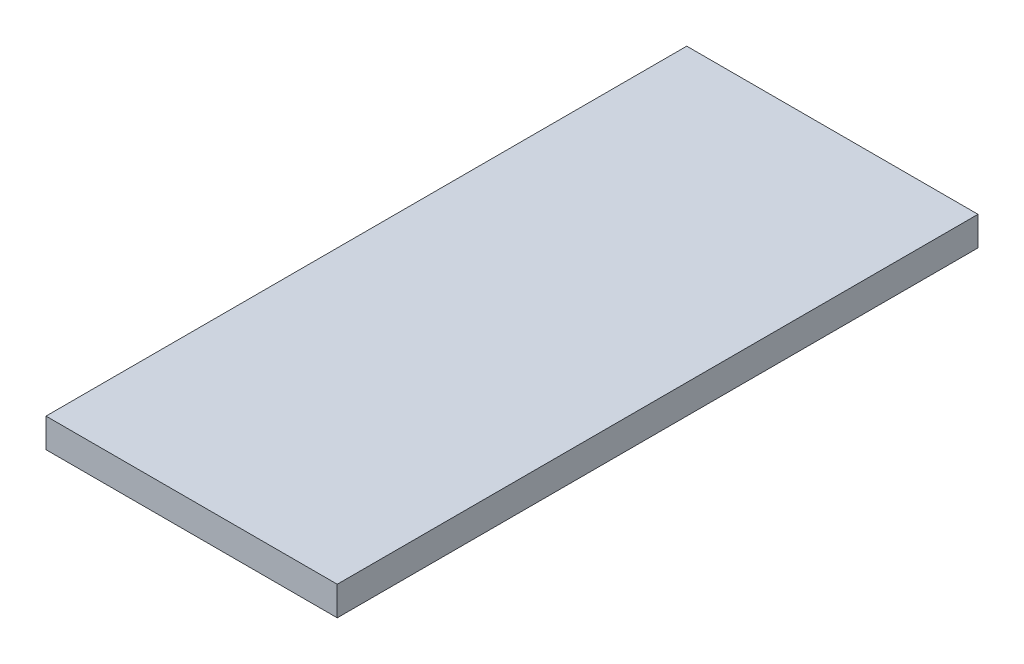
SolidWorks part; units mm, degrees
ref_plane "Front Plane" through (0, 0, 0) normal (0, 0, 1) x (1, 0, 0)
ref_plane "Top Plane" through (0, 0, 0) normal (0, 1, 0) x (1, 0, 0)
ref_plane "Right Plane" through (0, 0, 0) normal (1, 0, 0) x (0, 0, -1)
sketch "Sketch1" plane through (0, 0, 0) normal (0, 1, 0) x (1, 0, 0)
  line L1 (0, 0) -> (10, 0)
  line L2 (0, 0) -> (0, -22)
  line L3 (0, -22) -> (10, -22)
  line L4 (10, 0) -> (10, -22)
  dimension "D1" = 10
  dimension "D2" = 22
extrude "Boss-Extrude1" add sketch "Sketch1" along normal blind 1
